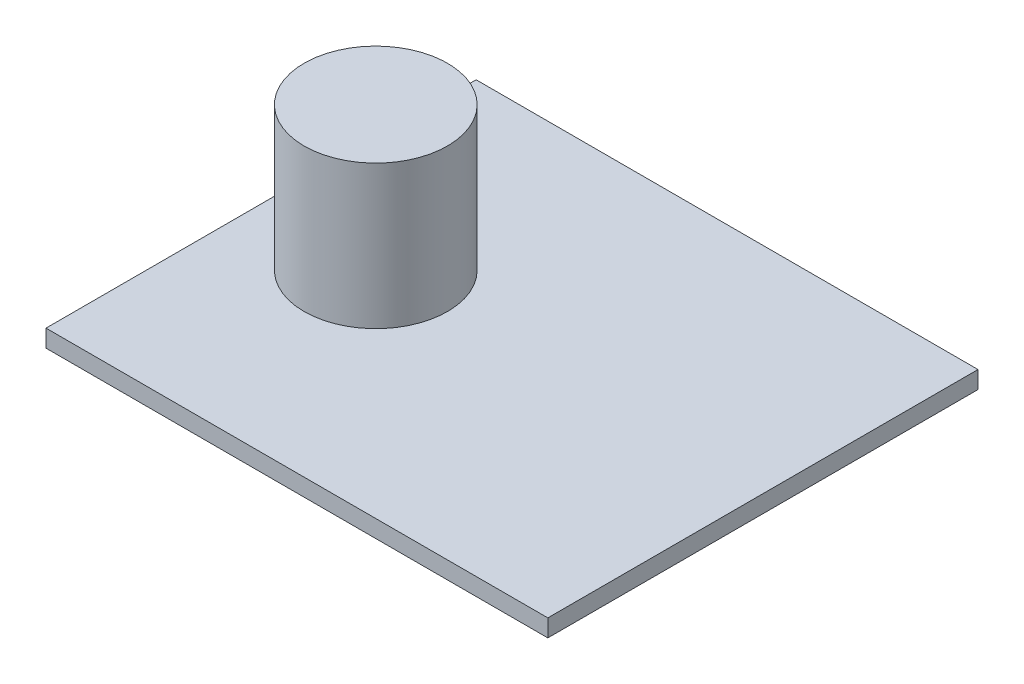
SolidWorks part; units mm, degrees
ref_plane "Front Plane" through (0, 0, 0) normal (0, 0, 1) x (1, 0, 0)
ref_plane "Top Plane" through (0, 0, 0) normal (0, 1, 0) x (1, 0, 0)
ref_plane "Right Plane" through (0, 0, 0) normal (1, 0, 0) x (0, 0, -1)
sketch "Sketch1" plane through (0, 0, 0) normal (0, 1, 0) x (1, 0, 0)
  line L1 (-99.2128, 37.0639) -> (-54.7628, 37.0639)
  line L2 (-99.2128, 37.0639) -> (-99.2128, -1.0361)
  line L3 (-99.2128, -1.0361) -> (-54.7628, -1.0361)
  line L4 (-54.7628, 37.0639) -> (-54.7628, -1.0361)
  dimension "D1" = 44.45
  dimension "D2" = 38.1
extrude "Boss-Extrude1" add sketch "Sketch1" along normal blind 12.7
sketch "Sketch2" plane through (0, 0, 1.0361) normal (0, 0, 1) x (1, 0, 0)
  line L0 (-99.2128, 0) -> (-99.2128, 1.5392)
  line L1 (-99.2128, 12.7) -> (-99.2128, 0) construction
  line L2 (-99.2128, 1.5392) -> (-54.7628, 1.5392)
  line L3 (-54.7628, 12.7) -> (-54.7628, 0) construction
  line L4 (-54.7628, 1.5392) -> (-54.7628, 0)
  line L5 (-54.7628, 0) -> (-99.2128, 0)
  dimension "D1" = 1.5392
sketch "Sketch4" plane through (0, 0, -37.0639) normal (0, 0, -1) x (-1, 0, 0)
  line L4 (99.2128, 0) -> (99.2128, 1.5392)
  line L5 (99.2128, 1.5392) -> (54.7628, 1.5392)
  line L6 (54.7628, 1.5392) -> (54.7628, 0)
  line L7 (54.7628, 0) -> (99.2128, 0)
  line L8 (99.2128, 0) -> (99.2128, 1.5392)
  line L9 (99.2128, 1.5392) -> (54.7628, 1.5392)
  line L10 (54.7628, 1.5392) -> (54.7628, 0)
  line L11 (54.7628, 0) -> (99.2128, 0)
  line M6 (99.2128, 0) -> (99.2128, 12.7)
  line M7 (99.2128, 12.7) -> (54.7628, 12.7)
  line M8 (54.7628, 12.7) -> (54.7628, 0)
  dimension "D1" = 0
extrude "Cut-Extrude1" cut sketch "Sketch4" against normal through all contours L9 M6 M7 M8
sketch "Sketch5" plane through (0, 1.5392, 0) normal (0, 1, 0) x (1, 0, 0)
  line L0 (-99.2128, 37.0639) -> (-54.7628, 37.0639) construction
  line L1 (-99.2128, -1.0361) -> (-99.2128, 37.0639) construction
  circle A0 centre (-89.0528, 18.0139) radius 6.35
  dimension "D1" = 12.7
  dimension "D2" = 19.05
  dimension "D3" = 10.16
extrude "Boss-Extrude2" add sketch "Sketch5" along normal blind 12.7
